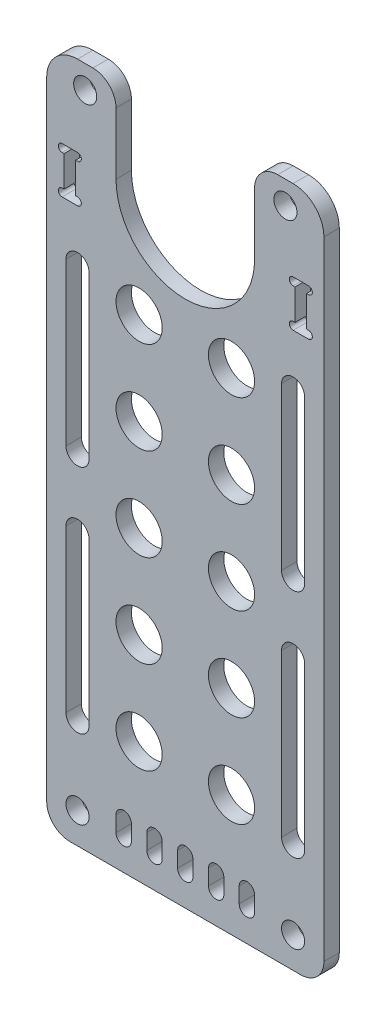
SolidWorks part; units mm, degrees
material "Carbon Fiber"
ref_plane "Front Plane" through (0, 0, 0) normal (0, 0, 1) x (1, 0, 0)
ref_plane "Top Plane" through (0, 0, 0) normal (0, 1, 0) x (1, 0, 0)
ref_plane "Right Plane" through (0, 0, 0) normal (1, 0, 0) x (0, 0, -1)
sketch "Sketch1" plane through (0, 0, 0) normal (0, 0, 1) x (1, 0, 0)
  line L0 (-14, 29.5) -> (14, -29.5) construction
  line L2 (-14, 29.5) -> (-14, -29.5) construction
  line L3 (-14, -29.5) -> (14, -29.5) construction
  line L4 (14, 29.5) -> (14, -29.5) construction
  line L5 (-18, 29.5) -> (-18, -33.5)
  line L6 (-18, -33.5) -> (18, -33.5)
  line L7 (18, 29.5) -> (18, -33.5)
  line L8 (-14, 52) -> (14, 52) construction
  line L9 (0, 0) -> (0, 52) construction
  line L10 (-14, 29.5) -> (-14, 52) construction
  line L11 (14, 29.5) -> (14, 52) construction
  line L12 (-14, 55) -> (-9, 55)
  line L13 (14, 29.5) -> (14, 52) construction
  line L14 (0, 0) -> (25.8882, 25.8882) construction
  line L15 (-9, 44) -> (-9, 55)
  line L16 (9, 44) -> (9, 55)
  line L17 (9, 55) -> (14, 55)
  line L19 (18, 29.5) -> (18, 51)
  line L20 (-18, 51) -> (-18, 29.5)
  circle A8 centre (-14, -29.5) radius 1.5
  circle A9 centre (14, -29.5) radius 1.5
  arc A14 (-9, 44) -> (9, 44) centre (0, 44) ccw
  arc A15 (-18, 51) -> (-14, 55) centre (-14, 51) cw
  arc A16 (18, 51) -> (14, 55) centre (14, 51) ccw
  circle A17 centre (-13, 52) radius 1.5
  circle A18 centre (13, 52) radius 1.5
  point P4 (0, 0)
  point P23 (0, 60.5)
  point P38 (0, 0)
  dimension "D5" = 1
  dimension "D6" = 3
  dimension "D9" = 3
  dimension "D10" = 3
  dimension "D16" = 18
  dimension "D17" = 3
  dimension "D1" = 28
  dimension "D2" = 81.5
  dimension "D3" = 4
  dimension "D4" = 63
  dimension "D11" = 45
  dimension "D15" = 8
extrude "Boss-Extrude1" add sketch "Sketch1" along normal blind 2
fillet "Fillet1" radius 3 2 edges at (18, -33.5, 1) (-18, -33.5, 1)
fillet "Fillet2" radius 3 2 edges at (9, 55, 1) (-9, 55, 1)
sketch "Sketch2" plane through (0, 0, 2) normal (0, 0, 1) x (1, 0, 0)
  line L0 (0, 0) -> (0, 34.0801) construction
  line L1 (-14, -29.5) -> (-14, -6.4291) construction
  line L2 (-15.5, 1.75) -> (-15.5, -19.25)
  line L3 (-12.5, 1.75) -> (-12.5, -19.25)
  line L4 (12.5, 1.75) -> (12.5, -19.25)
  line L5 (15.5, 1.75) -> (15.5, -19.25)
  line L6 (-15.5, 31.75) -> (-15.5, 10.75)
  line L7 (-12.5, 31.75) -> (-12.5, 10.75)
  line L8 (12.5, 31.75) -> (12.5, 10.75)
  line L9 (15.5, 31.75) -> (15.5, 10.75)
  line L10 (14, -20.75) -> (-14, -20.75) construction
  line L11 (-14, -29.5) -> (14, -29.5) construction
  line L12 (-8, -29.5) -> (-8, -27.5) construction
  line L13 (-9, -29.5) -> (-9, -27.5)
  line L14 (-7, -29.5) -> (-7, -27.5)
  line L15 (-4, -29.5) -> (-4, -27.5) construction
  line L16 (-5, -29.5) -> (-5, -27.5)
  line L17 (-3, -29.5) -> (-3, -27.5)
  line L18 (0, -29.5) -> (0, -27.5) construction
  line L19 (-1, -29.5) -> (-1, -27.5)
  line L20 (1, -29.5) -> (1, -27.5)
  line L21 (4, -29.5) -> (4, -27.5) construction
  line L22 (3, -29.5) -> (3, -27.5)
  line L23 (5, -29.5) -> (5, -27.5)
  line L24 (8, -29.5) -> (8, -27.5) construction
  line L25 (7, -29.5) -> (7, -27.5)
  line L26 (9, -29.5) -> (9, -27.5)
  line L27 (-16, 44) -> (-14, 44) construction
  line L28 (-16, 44.5) -> (-14, 44.5)
  line L29 (-16, 43.5) -> (-15.75, 43.5)
  line L30 (-9, 44) -> (-19.3716, 44) construction
  line L31 (-16, 39) -> (-14, 39) construction
  line L32 (-16, 39.5) -> (-15.75, 39.5)
  line L33 (-16, 38.5) -> (-14, 38.5)
  line L34 (-15.75, 43.5) -> (-15.75, 39.5)
  line L35 (-15, 44) -> (-15, 46.0576) construction
  line L36 (-14.25, 43.5) -> (-14.25, 39.5)
  line L37 (-14.25, 43.5) -> (-14, 43.5)
  line L38 (-14.25, 39.5) -> (-14, 39.5)
  line L39 (15, 44) -> (15, 46.0576) construction
  line L40 (16, 39) -> (14, 39) construction
  line L41 (16, 44) -> (14, 44) construction
  line L42 (14.25, 39.5) -> (14, 39.5)
  line L43 (14.25, 43.5) -> (14, 43.5)
  line L44 (14.25, 43.5) -> (14.25, 39.5)
  line L45 (15.75, 43.5) -> (15.75, 39.5)
  line L46 (16, 38.5) -> (14, 38.5)
  line L47 (16, 39.5) -> (15.75, 39.5)
  line L48 (16, 43.5) -> (15.75, 43.5)
  line L49 (16, 44.5) -> (14, 44.5)
  arc A0 (-12.5, 1.75) -> (-15.5, 1.75) centre (-14, 1.75) ccw
  arc A1 (-15.5, -19.25) -> (-12.5, -19.25) centre (-14, -19.25) ccw
  arc A2 (15.5, -19.25) -> (12.5, -19.25) centre (14, -19.25) cw
  arc A3 (12.5, 1.75) -> (15.5, 1.75) centre (14, 1.75) cw
  arc A4 (-12.5, 31.75) -> (-15.5, 31.75) centre (-14, 31.75) ccw
  arc A5 (-15.5, 10.75) -> (-12.5, 10.75) centre (-14, 10.75) ccw
  arc A6 (15.5, 10.75) -> (12.5, 10.75) centre (14, 10.75) cw
  arc A7 (12.5, 31.75) -> (15.5, 31.75) centre (14, 31.75) cw
  circle A8 centre (6, -17.75) radius 3
  circle A9 centre (-6, -17.75) radius 3
  circle A10 centre (-6, -5.75) radius 3
  circle A11 centre (6, -5.75) radius 3
  circle A12 centre (-6, 6.25) radius 3
  circle A13 centre (6, 6.25) radius 3
  circle A14 centre (-6, 18.25) radius 3
  circle A15 centre (6, 18.25) radius 3
  circle A16 centre (-6, 30.25) radius 3
  circle A17 centre (6, 30.25) radius 3
  arc A18 (-9, -29.5) -> (-7, -29.5) centre (-8, -29.5) ccw
  arc A19 (-7, -27.5) -> (-9, -27.5) centre (-8, -27.5) ccw
  arc A20 (-5, -29.5) -> (-3, -29.5) centre (-4, -29.5) ccw
  arc A21 (-3, -27.5) -> (-5, -27.5) centre (-4, -27.5) ccw
  arc A22 (-1, -29.5) -> (1, -29.5) centre (0, -29.5) ccw
  arc A23 (1, -27.5) -> (-1, -27.5) centre (0, -27.5) ccw
  arc A24 (3, -29.5) -> (5, -29.5) centre (4, -29.5) ccw
  arc A25 (5, -27.5) -> (3, -27.5) centre (4, -27.5) ccw
  arc A26 (7, -29.5) -> (9, -29.5) centre (8, -29.5) ccw
  arc A27 (9, -27.5) -> (7, -27.5) centre (8, -27.5) ccw
  arc A28 (-16, 44.5) -> (-16, 43.5) centre (-16, 44) ccw
  arc A29 (-14, 43.5) -> (-14, 44.5) centre (-14, 44) ccw
  arc A30 (-16, 39.5) -> (-16, 38.5) centre (-16, 39) ccw
  arc A31 (-14, 38.5) -> (-14, 39.5) centre (-14, 39) ccw
  arc A32 (14, 38.5) -> (14, 39.5) centre (14, 39) cw
  arc A33 (16, 39.5) -> (16, 38.5) centre (16, 39) cw
  arc A34 (14, 43.5) -> (14, 44.5) centre (14, 44) cw
  arc A35 (16, 44.5) -> (16, 43.5) centre (16, 44) cw
  point P56 (-8, -28.5)
  point P64 (-4, -28.5)
  point P71 (0, -28.5)
  point P78 (4, -28.5)
  point P85 (8, -28.5)
  point P91 (-15, 44)
  point P103 (-15, 46.0576)
  point P112 (-6, -14)
  point P122 (-15, 39)
  point P141 (15, 46.0576)
  point P142 (15, 44)
  dimension "D1" = 3
  dimension "D2" = 3
  dimension "D6" = 6
  dimension "D12" = 1
  dimension "D16" = 0.5
  dimension "D20" = 0.5
  dimension "D3" = 21
  dimension "D5" = 6
  dimension "D7" = 10.25
  dimension "D8" = 30
  dimension "D10" = 8
  dimension "D11" = 2
  dimension "D14" = 4
  dimension "D15" = 12
  dimension "D17" = 2
  dimension "D19" = 1.5
  dimension "D18" = 5
  dimension "D21" = 2
  dimension "D4" = 2
  dimension "D9" = 5
  dimension "D13" = 5
extrude "Cut-Extrude1" cut sketch "Sketch2" against normal through all
